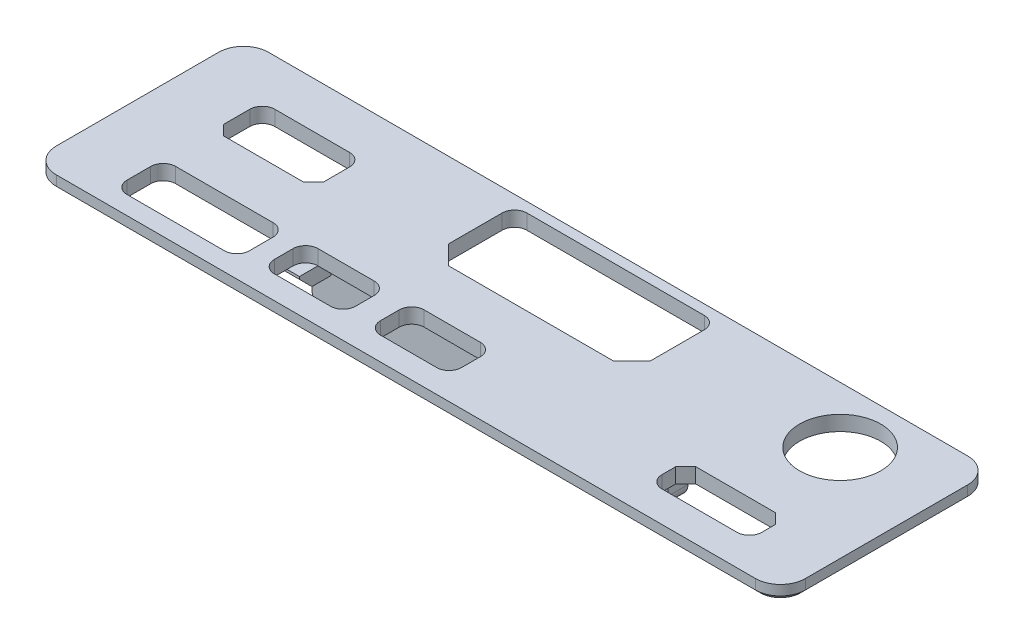
SolidWorks part; units mm, degrees
ref_plane "前视基准面" through (0, 0, 0) normal (0, 0, 1) x (1, 0, 0)
ref_plane "上视基准面" through (0, 0, 0) normal (0, 1, 0) x (1, 0, 0)
ref_plane "右视基准面" through (0, 0, 0) normal (1, 0, 0) x (0, 0, -1)
sketch "草图1" plane through (0, 0, 0) normal (0, 1, 0) x (1, 0, 0)
  line L1 (-30, 8.5) -> (30, 8.5)
  line L2 (-30, 8.5) -> (-30, -8.5)
  line L3 (-30, -8.5) -> (30, -8.5)
  line L4 (30, 8.5) -> (30, -8.5)
  line L5 (-30, 8.5) -> (30, -8.5) construction
  line L6 (-30, -8.5) -> (30, 8.5) construction
  point P0 (0, 0)
  dimension "D1" = 60
  dimension "D2" = 17
extrude "凸台-拉伸1" add sketch "草图1" along normal blind 1.2
sketch "草图4" plane through (0, 1.2, 0) normal (0, 1, 0) x (1, 0, 0)
  line L0 (-30, 8.5) -> (-30, -8.5) construction
  line L1 (-24.8, 4.8) -> (-16.8, 4.8)
  line L2 (-24.8, 4.8) -> (-24.8, 0.9)
  line L3 (-24.8, 0.9) -> (-16.8, 0.9)
  line L4 (-16.8, 4.8) -> (-16.8, 0.9)
  line L5 (-7.5, 7.7) -> (8.7, 7.7)
  line L6 (-7.5, 7.7) -> (-7.5, 0.9)
  line L7 (-7.5, 0.9) -> (8.7, 0.9)
  line L8 (8.7, 7.7) -> (8.7, 0.9)
  line L13 (17.05, -3.1348) -> (25.05, -3.1348)
  line L14 (17.05, -3.1348) -> (17.05, -6.0348)
  line L15 (17.05, -6.0348) -> (25.05, -6.0348)
  line L16 (25.05, -3.1348) -> (25.05, -6.0348)
  line L17 (-4.9, -3.1348) -> (1.6, -3.1348)
  line L18 (-4.9, -3.1348) -> (-4.9, -6.6348)
  line L19 (-4.9, -6.6348) -> (1.6, -6.6348)
  line L20 (1.6, -3.1348) -> (1.6, -6.6348)
  line L21 (-13.4, -3.1348) -> (-6.9, -3.1348)
  line L22 (-13.4, -3.1348) -> (-13.4, -6.6348)
  line L23 (-13.4, -6.6348) -> (-6.9, -6.6348)
  line L24 (-6.9, -3.1348) -> (-6.9, -6.6348)
  line L25 (-24.8, -3.1348) -> (-15, -3.1348)
  line L26 (-24.8, -3.1348) -> (-24.8, -7.0348)
  line L27 (-24.8, -7.0348) -> (-15, -7.0348)
  line L28 (-15, -3.1348) -> (-15, -7.0348)
  line L29 (30, 8.5) -> (-30, 8.5) construction
  line L31 (30, -8.5) -> (30, 8.5) construction
  line L32 (30, 8.5) -> (-30, 8.5) construction
  circle A0 centre (22.2985, 3.9832) radius 3.25
  point P8 (0, 0)
  point P9 (0, 0)
  point P10 (0, 0)
  point P11 (-7.5, 1.4)
  point P30 (-7.5, 4.9)
  point P35 (-7.5, 7.6377)
  point P36 (0, 0)
  point P39 (0, 0)
  dimension "D21" = 6.5
  dimension "D1" = 3.5
  dimension "D2" = 6.5
  dimension "D3" = 6.5
  dimension "D4" = 3.5
  dimension "D5" = 8
  dimension "D6" = 3.9
  dimension "D7" = 16.2
  dimension "D8" = 8
  dimension "D9" = 2.9
  dimension "D10" = 5.2
  dimension "D11" = 7.6
  dimension "D12" = 11.6348
  dimension "D13" = 16.6
  dimension "D14" = 25.1
  dimension "D15" = 4.95
  dimension "D16" = 9.8
  dimension "D17" = 22.5
  dimension "D19" = 7.7015
  dimension "D20" = 4.5168
  dimension "D22" = 6.8
extrude "切除-拉伸1" cut sketch "草图4" against normal up to next
fillet "圆角2" radius 1 18 edges at (-24.8, 0.6, -4.8) (-16.8, 0.6, -4.8) (8.7, 0.6, -7.7) (-7.5, 0.6, -7.7) (25.05, 0.6, 6.0348) (17.05, 0.6, 6.0348) (1.6, 0.6, 6.6348) (1.6, 0.6, 3.1348) (-4.9, 0.6, 3.1348) (-4.9, 0.6, 6.6348) (-6.9, 0.6, 6.6348) (-6.9, 0.6, 3.1348) (-13.4, 0.6, 3.1348) (-13.4, 0.6, 6.6348) (-15, 0.6, 7.0348) (-15, 0.6, 3.1348) (-24.8, 0.6, 3.1348) (-24.8, 0.6, 7.0348)
chamfer "倒角1" distance 0.8 angle 45 4 edges at (17.05, 0.6, 3.1348) (25.05, 0.6, 3.1348) (-16.8, 0.6, -0.9) (-24.8, 0.6, -0.9)
sketch "草图5" plane through (0, 0, 0) normal (0, -1, 0) x (1, 0, 0)
  line L0 (-30, -8.5) -> (-30, 8.5) construction
  line L1 (-13.9089, -3.3832) -> (-12.4089, -3.3832)
  line L2 (-13.9089, -3.3832) -> (-13.9089, 4.6168)
  line L3 (-13.9089, 4.6168) -> (-12.4089, 4.6168)
  line L4 (-12.4089, -3.3832) -> (-12.4089, 4.6168)
  line L5 (13.0911, -3.3832) -> (14.5911, -3.3832)
  line L6 (13.0911, -3.3832) -> (13.0911, 4.6168)
  line L7 (13.0911, 4.6168) -> (14.5911, 4.6168)
  line L8 (14.5911, -3.3832) -> (14.5911, 4.6168)
  line L9 (30, -8.5) -> (-30, -8.5) construction
  line L10 (30, 8.5) -> (30, -8.5) construction
  dimension "D1" = 1.5
  dimension "D2" = 8
  dimension "D3" = 1.5
  dimension "D4" = 8
  dimension "D5" = 16.0911
  dimension "D6" = 5.1168
  dimension "D7" = 5.1168
  dimension "D8" = 15.4089
extrude "凸台-拉伸2" add sketch "草图5" along normal blind 1.2
sketch "草图6" plane through (0, 0, 0) normal (0, -1, 0) x (1, 0, 0)
  line L0 (-13.9089, 4.6168) -> (-13.9089, -3.3832) construction
  line L1 (-13.9089, 2.1) -> (14.5911, 2.1)
  line L2 (-13.9089, 2.1) -> (-13.9089, 0.5)
  line L3 (-13.9089, 0.5) -> (14.5911, 0.5)
  line L4 (14.5911, 2.1) -> (14.5911, 0.5)
  line L5 (30, -8.5) -> (-30, -8.5) construction
  dimension "D1" = 1.6
  dimension "D2" = 9
extrude "凸台-拉伸3" add sketch "草图6" along normal blind 4
fillet "圆角3" radius 1 2 edges at (14.5911, -4, 1.3) (-13.9089, -4, 1.3)
chamfer "倒角2" distance 1 angle 45 4 edges at (13.8411, -1.2, -3.3832) (-13.1589, -1.2, -3.3832) (13.8411, -1.2, 4.6168) (-13.1589, -1.2, 4.6168)
fillet "圆角4" radius 2 4 edges at (30, 0.6, 8.5) (30, 0.6, -8.5) (-30, 0.6, 8.5) (-30, 0.6, -8.5)
chamfer "倒角5" distance 0.4 angle 45 8 edges at (0, 0, -8.5) (-29.4142, 0, -7.9142) (29.4142, 0, -7.9142) (-30, 0, 0) (30, 0, 0) (-29.4142, 0, 7.9142) (29.4142, 0, 7.9142) (0, 0, 8.5)
chamfer "倒角6" distance 1.5 angle 45 2 edges at (8.7, 0.6, -0.9) (-7.5, 0.6, -0.9)
